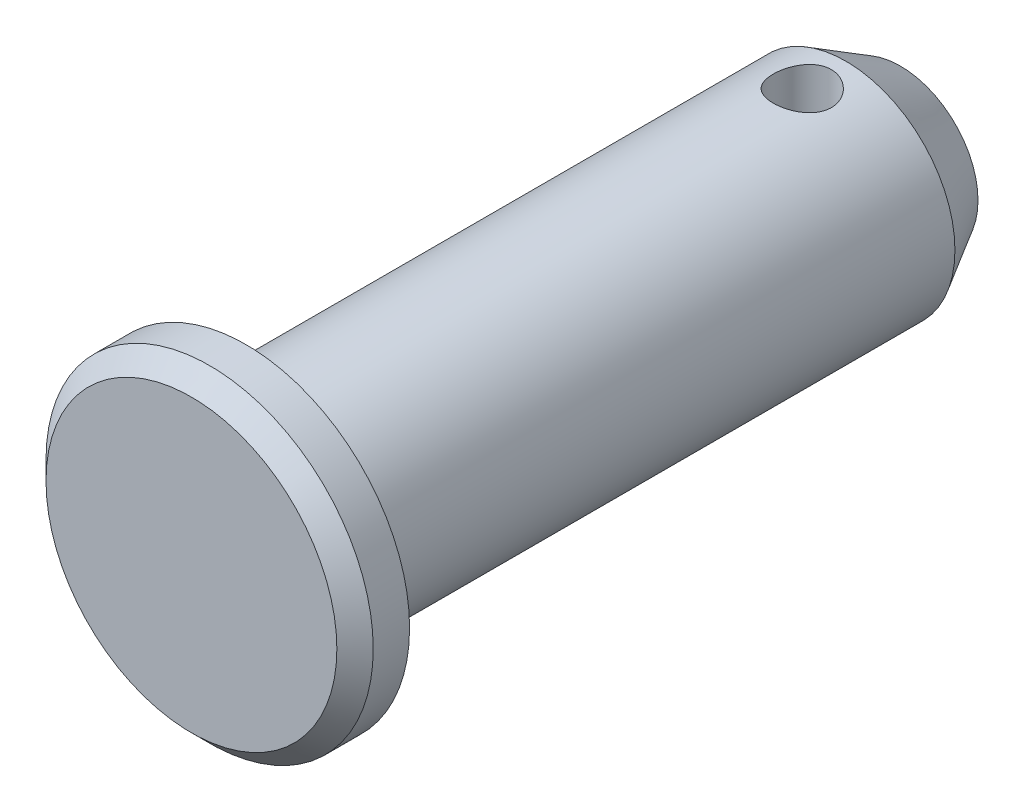
SolidWorks part; units mm, degrees
material "1.0545 (S355N)"
ref_plane "Płaszczyzna przednia" through (0, 0, 0) normal (0, 0, 1) x (1, 0, 0)
ref_plane "Płaszczyzna górna" through (0, 0, 0) normal (0, 1, 0) x (1, 0, 0)
ref_plane "Płaszczyzna prawa" through (0, 0, 0) normal (1, 0, 0) x (0, 0, -1)
sketch "Szkic1" plane through (0, 0, 0) normal (0, 1, 0) x (1, 0, 0)
  line L0 (4, -9.75) -> (-4, -9.75)
  line L1 (-4.5, -9.25) -> (-4.5, -8.25)
  line L2 (-4.5, -8.25) -> (-3, -8.25)
  line L3 (-3, -8.25) -> (-3, 8.25)
  line L4 (-2.134, 9.75) -> (2.134, 9.75)
  line L5 (3, 8.25) -> (3, -8.25)
  line L6 (3, -8.25) -> (4.5, -8.25)
  line L7 (4.5, -8.25) -> (4.5, -9.25)
  line L8 (4.5, -9.25) -> (4, -9.75)
  line L9 (-4, -9.75) -> (-4.5, -9.25)
  line L10 (2.134, 9.75) -> (3, 8.25)
  line L11 (-3, 8.25) -> (-2.134, 9.75)
  line L12 (0, -9.75) -> (0, 9.75)
  point P0 (4.5, -9.75)
  point P1 (-4.5, -9.75)
  point P5 (-3, 9.75)
  point P6 (3, 9.75)
  point P7 (0, 0)
  point P17 (0, 9.75)
  point P19 (0, -9.75)
  dimension "D1" = 9
  dimension "D2" = 6
  dimension "D3" = 1.5
  dimension "D4" = 30
  dimension "D8" = 30
  dimension "D9" = 18
  dimension "D10" = 1.5
revolve "Obrót1" add sketch "Szkic1" angle 360 about L12
sketch "Szkic2" plane through (0, 0, 0) normal (0, 1, 0) x (1, 0, 0)
  line L0 (3, -8.25) -> (-3, -8.25) construction
  circle A0 centre (0, 7.05) radius 0.8
  dimension "D2" = 1.6
  dimension "D1" = 15.3
extrude "Wytnij-wyciągnięcie1" cut sketch "Szkic2" against normal through all both and the other way through all contours A0
